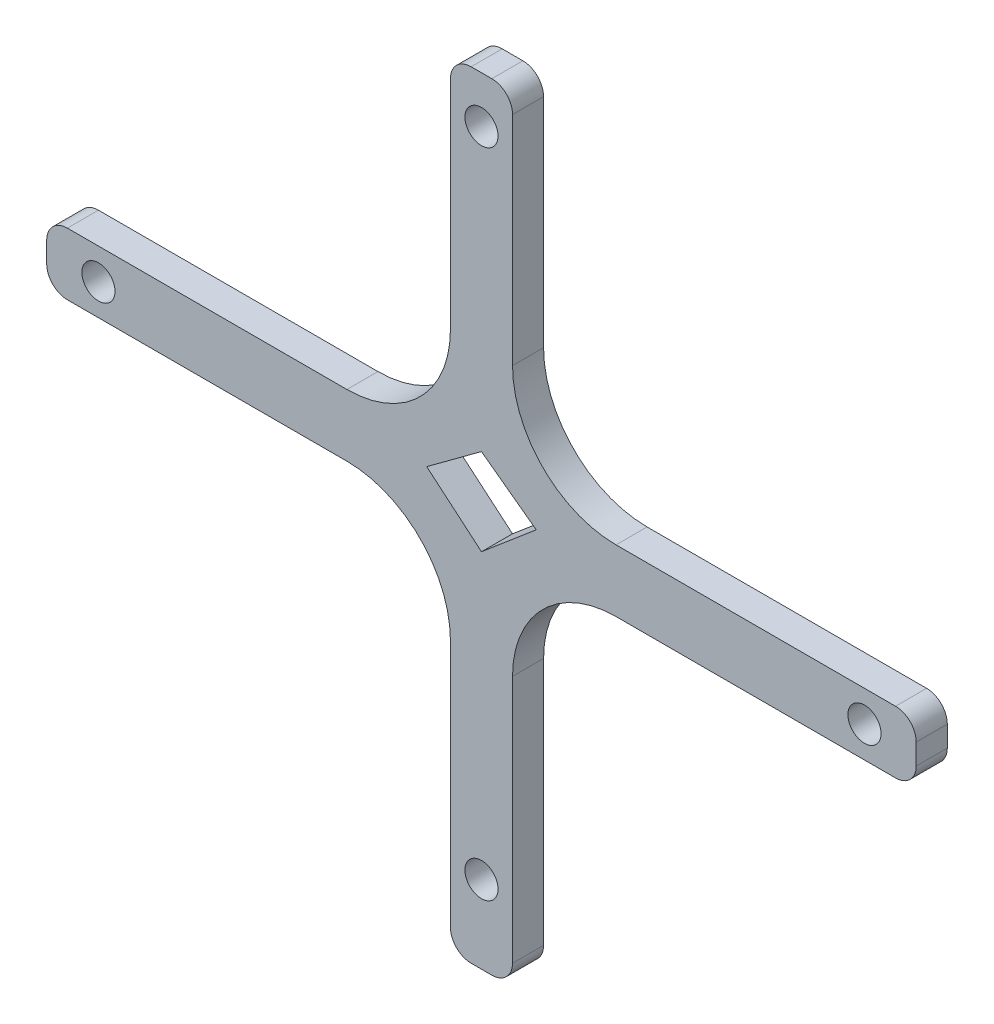
SolidWorks part; units mm, degrees
ref_plane "前视基准面" through (0, 0, 0) normal (0, 0, 1) x (1, 0, 0)
ref_plane "上视基准面" through (0, 0, 0) normal (0, 1, 0) x (1, 0, 0)
ref_plane "右视基准面" through (0, 0, 0) normal (1, 0, 0) x (0, 0, -1)
other "Configuration Table"
sketch "草图1" plane through (0, 0, 0) normal (0, 0, 1) x (1, 0, 0)
  line L0 (3, 43.3061) -> (-2.2889, 39.4014)
  line L1 (0, 0) -> (6, 0)
  line L2 (0, 0) -> (0, 36)
  line L3 (0, 75) -> (6, 75)
  line L4 (6, 0) -> (6, 36)
  line L5 (-39, 42) -> (0, 42)
  line L6 (-39, 42) -> (-39, 36)
  line L7 (-39, 36) -> (0, 36)
  line L8 (45, 42) -> (45, 36)
  line L9 (3, 75) -> (3, 3) construction
  line L10 (6, 42) -> (45, 42)
  line L11 (6, 36) -> (45, 36)
  line L12 (6, 42) -> (6, 75)
  line L13 (0, 42) -> (0, 75)
  line L14 (3, 39) -> (19.7701, 39) construction
  line L15 (-2.2889, 39.4014) -> (3, 34.9269)
  line L16 (8.2889, 39.4014) -> (3, 34.9269)
  line L17 (3, 43.3061) -> (8.2889, 39.4014)
  circle A0 centre (40, 39) radius 1.6
  circle A1 centre (-34, 39) radius 1.6
  circle A2 centre (3, 7.5) radius 1.6
  circle A3 centre (3, 70.5) radius 1.6
  dimension "D7" = 3.2
  dimension "D1" = 75
  dimension "D2" = 84
  dimension "D3" = 6
  dimension "D4" = 6
  dimension "D5" = 39
  dimension "D6" = 63
  dimension "D8" = 74
extrude "凸台-拉伸1" add sketch "草图1" along normal blind 3
fillet "圆角1" radius 2 8 edges at (0, 0, 1.5) (-39, 36, 1.5) (-39, 42, 1.5) (6, 0, 1.5) (45, 36, 1.5) (45, 42, 1.5) (6, 75, 1.5) (0, 75, 1.5)
fillet "圆角2" radius 10 4 edges at (6, 36, 1.5) (0, 36, 1.5) (0, 42, 1.5) (6, 42, 1.5)
